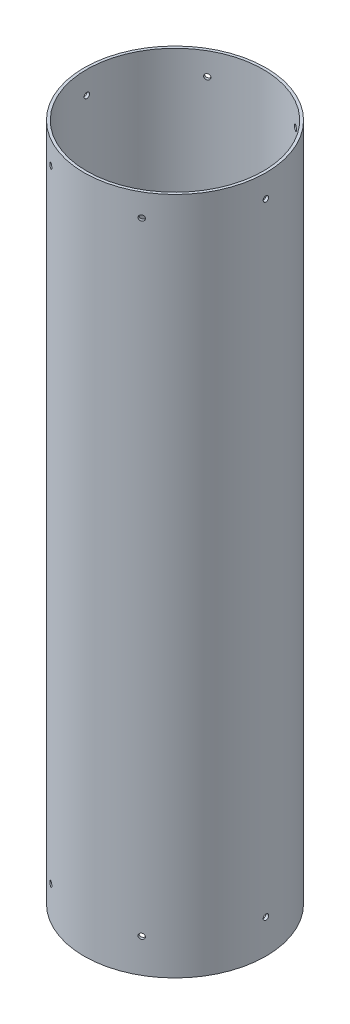
SolidWorks part; units mm, degrees
ref_plane "Front Plane" through (0, 0, 0) normal (0, 0, 1) x (1, 0, 0)
ref_plane "Top Plane" through (0, 0, 0) normal (0, 1, 0) x (1, 0, 0)
ref_plane "Right Plane" through (0, 0, 0) normal (1, 0, 0) x (0, 0, -1)
sketch "Sketch1" plane through (0, 0, 0) normal (0, 1, 0) x (1, 0, 0)
  circle A0 centre (0, 0) radius 51.054
  circle A1 centre (0, 0) radius 49.53
  dimension "D1" = 99.06
  dimension "D2" = 102.108
extrude "Boss-Extrude1" add sketch "Sketch1" along normal blind 381
sketch "Sketch2" plane through (0, 0, 0) normal (1, 0, 0) x (0, 0, -1)
  line L0 (0, 0) -> (0, 17.526)
  line L1 (0, 17.526) -> (0, 19.05)
  circle A0 centre (0, 19.05) radius 1.524
  dimension "D2" = 3.048
  dimension "D1" = 17.526
extrude "Cut-Extrude1" cut sketch "Sketch2" against normal blind 136.398
pattern_circular "CirPattern1" count 6 over 360 about axis through (0, 381, 0) along (0, -1, 0) of "Cut-Extrude1"
sketch "Sketch3" plane through (0, 0, 0) normal (1, 0, 0) x (0, 0, -1)
  line L0 (0, 381) -> (0, 369.824)
  line L1 (51.054, 381) -> (-51.054, 381) construction
  line L2 (0, 369.824) -> (0, 368.3)
  circle A0 centre (0, 368.3) radius 1.524
  dimension "D2" = 3.048
  dimension "D1" = 11.176
extrude "Cut-Extrude2" cut sketch "Sketch3" against normal blind 177.8
pattern_circular "CirPattern2" count 6 over 360 about axis through (0, 381, 0) along (0, -1, 0) of "Cut-Extrude2"
